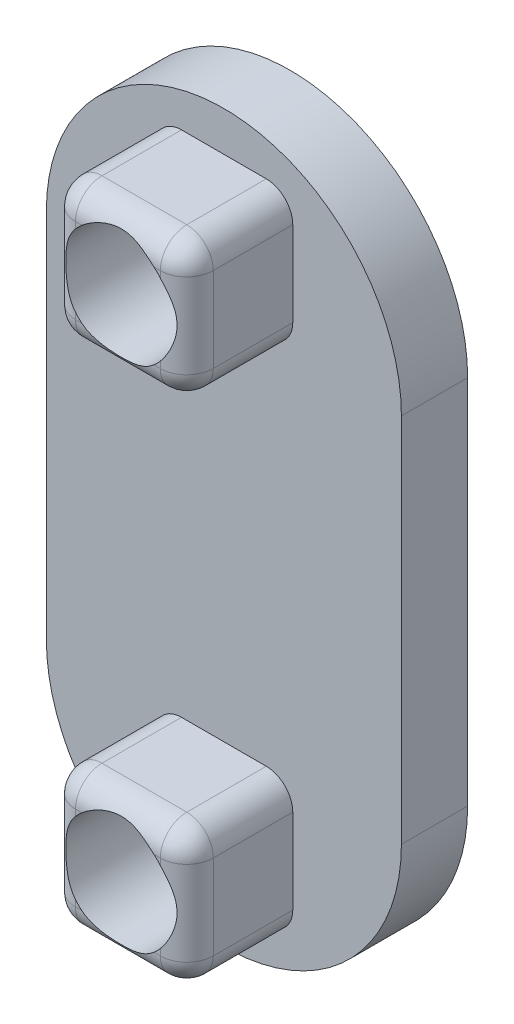
SolidWorks part; units mm, degrees
ref_plane "Front Plane" through (0, 0, 0) normal (1, 0, 0) x (0, 1, 0)
ref_plane "Top Plane" through (0, 0, 0) normal (0, 0, 1) x (0, 1, 0)
ref_plane "Right Plane" through (0, 0, 0) normal (0, 1, 0) x (-1, 0, 0)
sketch "Sketch1" plane through (0, 0, 0) normal (0, 0, 1) x (0, 1, 0)
  line L0 (0, 0) -> (14, 0) construction
  line L5 (0, 6.7) -> (14, 6.7)
  line L6 (0, -6.7) -> (14, -6.7)
  arc A0 (0, 6.7) -> (0, -6.7) centre (0, 0) ccw
  arc A1 (14, -6.7) -> (14, 6.7) centre (14, 0) ccw
  point P2 (7, 0)
  dimension "D1" = 14
  dimension "D2" = 13.4
extrude "Boss-Extrude1" add sketch "Sketch1" along normal blind 2.5
sketch "Sketch2" plane through (0, 0, 2.5) normal (0, 0, 1) x (1, 0, 0)
  line L0 (0, 0) -> (0, 14) construction
  line L1 (-2.6, 0) -> (2.6, 0)
  line L2 (-2.6, 0) -> (-2.6, -5.2)
  line L3 (-2.6, -5.2) -> (2.6, -5.2)
  line L4 (2.6, 0) -> (2.6, -5.2)
  line L5 (0, 7) -> (-6.7, 7) construction
  line L6 (-6.7, 0) -> (-6.7, 14) construction
  line L7 (2.6, 14) -> (2.6, 19.2)
  line L8 (-2.6, 19.2) -> (2.6, 19.2)
  line L9 (-2.6, 14) -> (-2.6, 19.2)
  line L10 (-2.6, 14) -> (2.6, 14)
  dimension "D1" = 5.2
  dimension "D2" = 5.2
  dimension "D3" = 2.6
  dimension "D4" = 0
extrude "Boss-Extrude2" add sketch "Sketch2" along normal blind 4
fillet "Fillet1" radius 1 16 edges at (0, 0, 6.5) (2.6, -2.6, 6.5) (-2.6, -2.6, 6.5) (0, -5.2, 6.5) (2.6, 0, 4.5) (-2.6, 0, 4.5) (-2.6, -5.2, 4.5) (2.6, -5.2, 4.5) (-2.6, 16.6, 6.5) (-2.6, 14, 4.5) (0, 14, 6.5) (0, 19.2, 6.5) (-2.6, 19.2, 4.5) (2.6, 14, 4.5) (2.6, 16.6, 6.5) (2.6, 19.2, 4.5)
sketch "Sketch3" plane through (0, 0, 6.5) normal (0, 0, 1) x (1, 0, 0)
  line L0 (-1.6, 16.6) -> (1.6, 16.6) construction
  line L3 (-1.6, 18.2) -> (-1.6, 15) construction
  line L4 (1.6, 15) -> (1.6, 18.2) construction
  line L5 (0, 15) -> (0, 18.2)
  line L6 (1.6, 18.2) -> (-1.6, 18.2) construction
  line L7 (-6.7, 7) -> (6.7, 7) construction
  line L8 (-6.7, 0) -> (-6.7, 14) construction
  line L9 (6.7, 0) -> (6.7, 14) construction
  line L10 (-1.6, -2.6) -> (1.6, -2.6) construction
  line L11 (0, -1) -> (0, -4.2)
  circle A0 centre (0, 16.6) radius 2.1
  circle A1 centre (0, -2.6) radius 2.1
  point P11 (0, 16.6)
  point P25 (0, -2.6)
  dimension "D1" = 4.2
extrude "Cut-Extrude1" cut sketch "Sketch3" against normal through all contours A1 | A0
